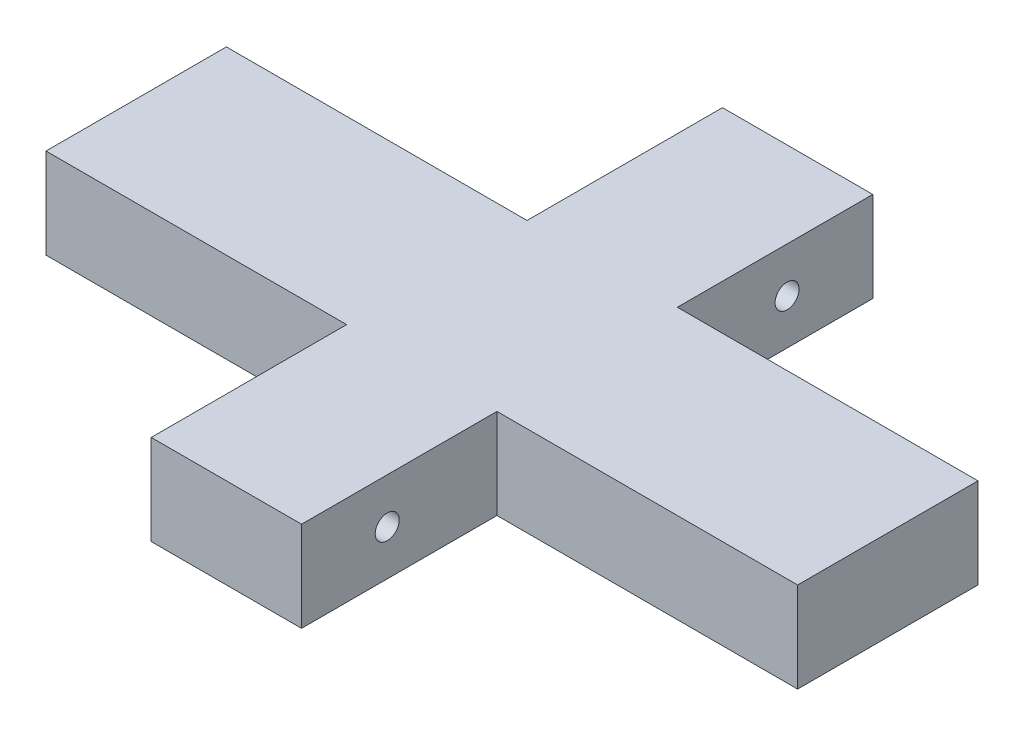
SolidWorks part; units mm, degrees
ref_plane "Front Plane" through (0, 0, 0) normal (0, 0, 1) x (1, 0, 0)
ref_plane "Top Plane" through (0, 0, 0) normal (0, 1, 0) x (1, 0, 0)
ref_plane "Right Plane" through (0, 0, 0) normal (1, 0, 0) x (0, 0, -1)
sketch "Sketch1" plane through (0, 0, 0) normal (0, 1, 0) x (1, 0, 0)
  line L0 (-250, 60) -> (-50, 60)
  line L1 (-250, 190) -> (250, 190) construction
  line L2 (-250, 190) -> (-250, -190) construction
  line L3 (-250, -190) -> (250, -190) construction
  line L4 (250, 190) -> (250, -190) construction
  line L5 (-250, 190) -> (250, -190) construction
  line L6 (-250, -190) -> (250, 190) construction
  line L7 (-50, 60) -> (-50, 190)
  line L8 (-50, 190) -> (50, 190)
  line L9 (50, 190) -> (50, 60)
  line L10 (50, 60) -> (250, 60)
  line L11 (250, 60) -> (250, -60)
  line L12 (250, -60) -> (50, -60)
  line L13 (50, -60) -> (50, -190)
  line L14 (50, -190) -> (-50, -190)
  line L15 (-50, -190) -> (-50, -60)
  line L16 (-50, -60) -> (-250, -60)
  line L17 (-250, 60) -> (-250, -60)
  point P0 (0, 0)
  dimension "D1" = 130
  dimension "D2" = 200
  dimension "D3" = 100
  dimension "D4" = 380
extrude "Boss-Extrude1" add sketch "Sketch1" along normal blind 60
sketch "Sketch2" plane through (-50, 0, 0) normal (-1, 0, 0) x (0, 0, 1)
  line L0 (190, 30) -> (133, 30) construction
  line L1 (-133, 30) -> (-125, 30) construction
  line L2 (190, 60) -> (190, 0) construction
  line L3 (-190, 30) -> (-133, 30) construction
  line L4 (133, 30) -> (125, 30) construction
  line L7 (-190, 60) -> (-190, 0) construction
  circle A0 centre (133, 30) radius 8
  circle A1 centre (-133, 30) radius 8
  point P15 (-123.6879, 30)
  dimension "D1" = 8
  dimension "D2" = 57
  dimension "D3" = 57
extrude "Cut-Extrude1" cut sketch "Sketch2" against normal through all both and the other way through all
sketch "Sketch3" plane through (50, 0, 0) normal (1, 0, 0) x (0, 0, -1)
  line L0 (-190, 0) -> (190, 0)
  line L1 (190, 0) -> (170.2972, -18.5356)
  line L2 (115.4808, -40.2677) -> (-115.4808, -40.2677)
  line L3 (-170.2972, -18.5356) -> (-190, 0)
  arc A0 (170.2972, -18.5356) -> (115.4808, -40.2677) centre (115.4808, 39.7323) cw
  arc A1 (-115.4808, -40.2677) -> (-170.2972, -18.5356) centre (-115.4808, 39.7323) cw
  dimension "D1" = 80
extrude "Boss-Extrude2" [suppressed] add sketch "Sketch3" against normal up to surface (72 mm away)
